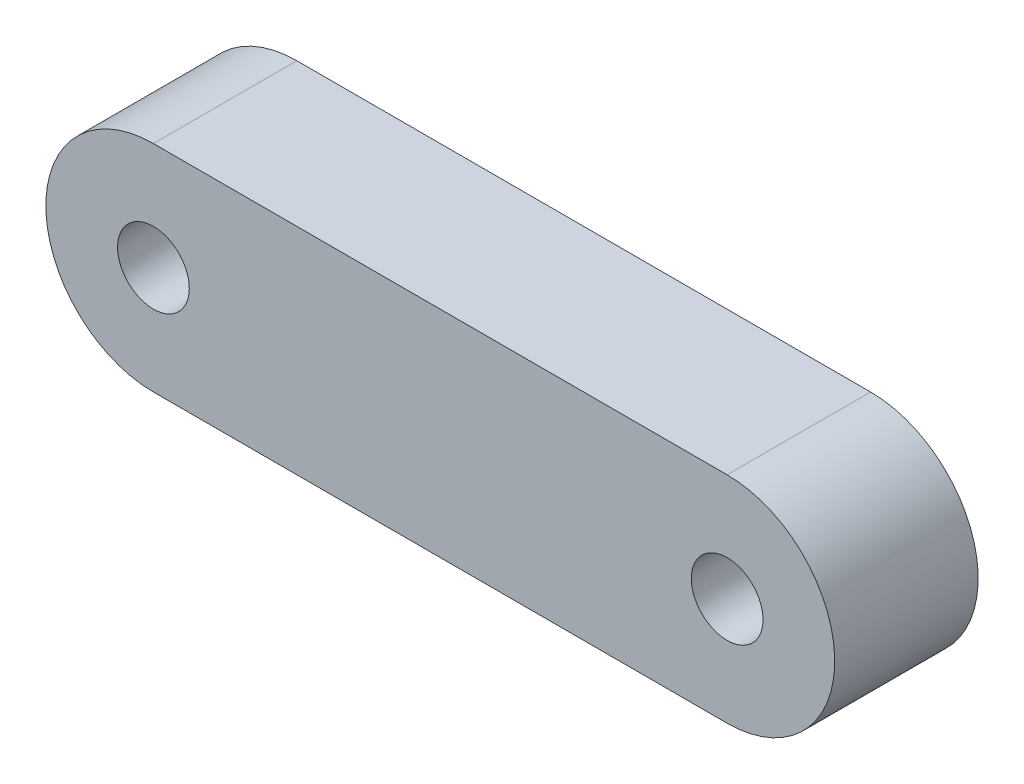
SolidWorks part; units mm, degrees
material "AISI 1020"
ref_plane "Front Plane" through (0, 0, 0) normal (0, 0, 1) x (1, 0, 0)
ref_plane "Top Plane" through (0, 0, 0) normal (0, 1, 0) x (1, 0, 0)
ref_plane "Right Plane" through (0, 0, 0) normal (1, 0, 0) x (0, 0, -1)
sketch "Sketch1" plane through (0, 0, 0) normal (0, 0, 1) x (1, 0, 0)
  line L0 (0, 0) -> (80, 0) construction
  line L1 (0, 15) -> (80, 15)
  line L2 (0, -15) -> (80, -15)
  arc A0 (0, 15) -> (0, -15) centre (0, 0) ccw
  arc A1 (80, -15) -> (80, 15) centre (80, 0) ccw
  circle A2 centre (80, 0) radius 5
  circle A3 centre (0, 0) radius 5
  point P3 (40, 0)
  dimension "D1" = 10
  dimension "D2" = 10
  dimension "D4" = 10
  dimension "D3" = 80
extrude "Boss-Extrude1" add sketch "Sketch1" along normal blind 20
